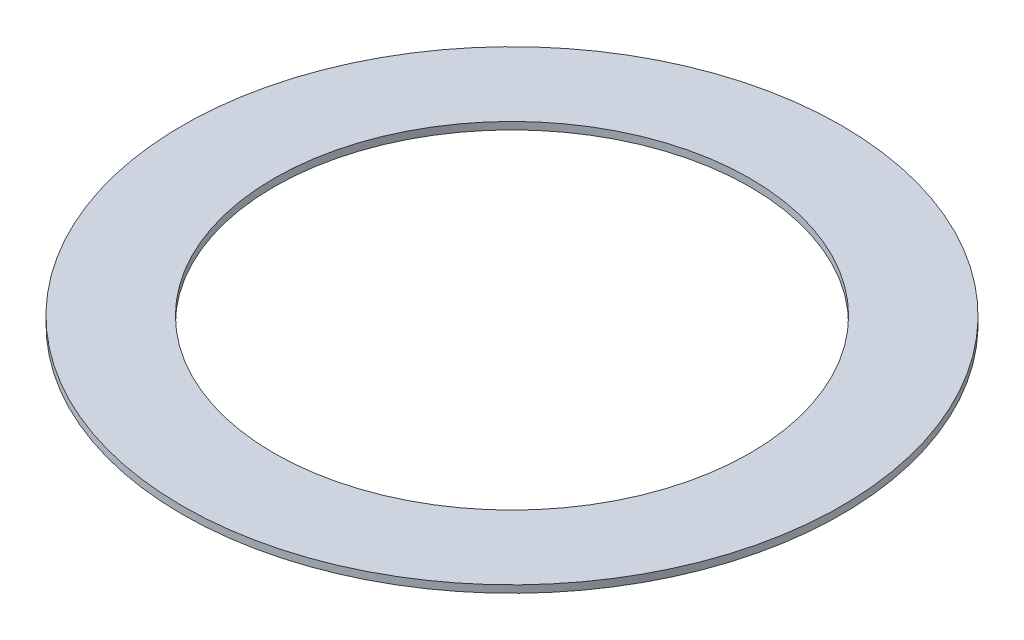
SolidWorks part; units mm, degrees
material "1.7131 (16MnCr5)"
ref_plane "前视基准面" through (0, 0, 0) normal (0, 0, 1) x (1, 0, 0)
ref_plane "上视基准面" through (0, 0, 0) normal (0, 1, 0) x (1, 0, 0)
ref_plane "右视基准面" through (0, 0, 0) normal (1, 0, 0) x (0, 0, -1)
sketch "草图1" plane through (0, 0, 0) normal (0, 1, 0) x (1, 0, 0)
  circle A0 centre (0, 0) radius 18
  dimension "D1" = 36
extrude "凸台-拉伸1" add sketch "草图1" along normal blind 0.4
sketch "草图2" plane through (0, 0.4, 0) normal (0, 1, 0) x (1, 0, 0)
  circle A0 centre (0, 0) radius 13
  dimension "D1" = 26
extrude "切除-拉伸1" cut sketch "草图2" against normal blind 0.4
